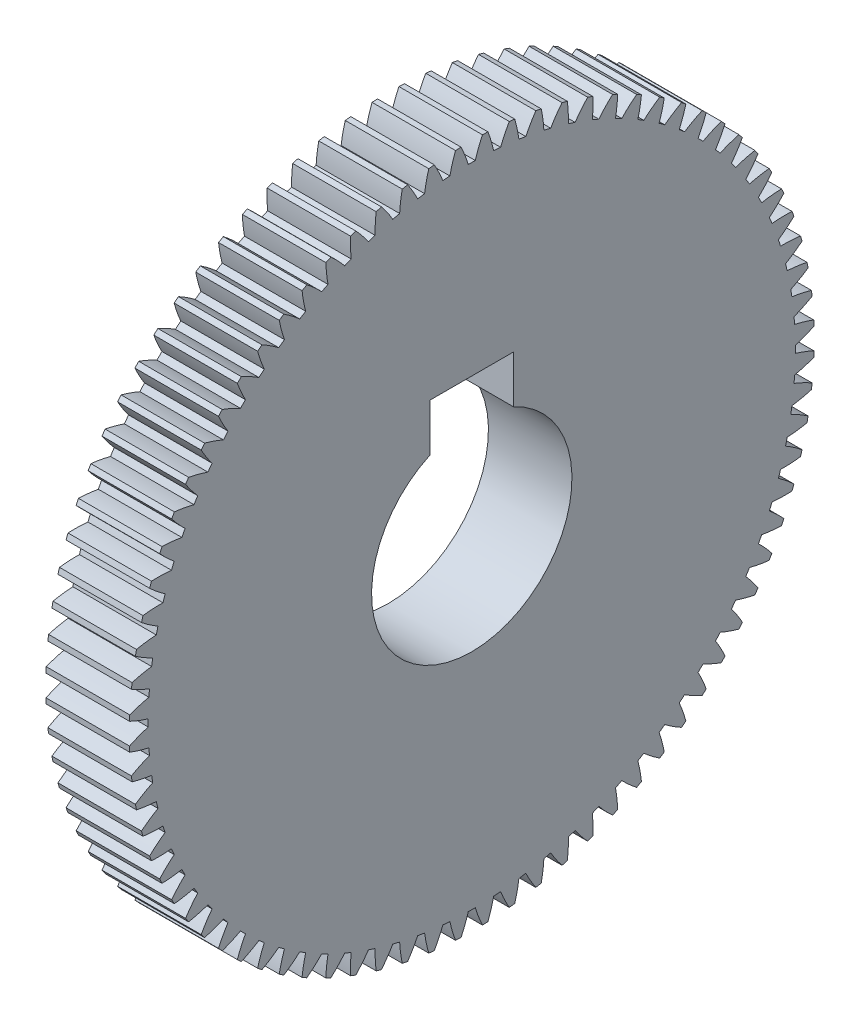
SolidWorks part; units mm, degrees
ref_plane "Plane1" through (0, 0, 0) normal (0, 0, 1) x (1, 0, 0)
ref_plane "Plane2" through (0, 0, 0) normal (0, 1, 0) x (1, 0, 0)
ref_plane "Plane3" through (0, 0, 0) normal (1, 0, 0) x (0, 0, -1)
other "Configuration Table"
sketch "HoldingSke" plane through (0, 0, 0) normal (0, 1, 0) x (1, 0, 0)
  line L0 (0, 0) -> (0.3473, -1.9696)
  line L1 (-15, 0) -> (100, 0) construction
  line L2 (0, 0) -> (-2.1039, 2.3779)
  line L3 (0, 0) -> (-11.863, 4.5341)
  line L4 (0, 0) -> (1.4996, 8.5048)
  line L5 (0, 0) -> (-46.8476, -17.4728)
  line L6 (0, 0) -> (-4.1448, -2.7965)
  line L7 (-2.1039, 2.3779) -> (8.6586, 51.2059)
  line L8 (-76.2, 54.61) -> (-73.9, 54.61)
  line L9 (-71.009, 38.7566) -> (-53.1078, 45.2721)
  line L10 (-76.2, 71.12) -> (104.1128, 71.12)
  line L11 (0, 0) -> (-5, 0)
  line L12 (-76.2, 101.6) -> (-76.181, 101.6)
  line L13 (24.9733, 27.94) -> (52.9518, 28.4284)
  line L14 (24.9733, 27.94) -> (24.9743, 27.94)
  line L15 (24.9733, 27.94) -> (100.4006, 29.5858)
  line L16 (-63.627, -0.5) -> (-12.827, -0.5)
  circle A0 centre (0, 0) radius 6
  circle A1 centre (0, 0) radius 19.374
  circle A2 centre (0, 0) radius 37.5
  circle A3 centre (0, 0) radius 6
  dimension "MHD" = 38.748
  dimension "Hub_dia" = 75
  dimension "Bore" = 12
  dimension "MBD" = 12
  dimension "Num_teeth" = 80
  dimension "Pitch" = 2
  dimension "Overall_len" = 50
  dimension "Show_teeth" = 80
  dimension "Thickness" = 5
  dimension "OAL" = 50.0001
  dimension "T_dim" = 2.3
  dimension "Ap" = 20
  dimension "H" = 19.05
  dimension "Pitch_radius" = 180.3128
  dimension "Width" = 5
  dimension "Backlash" = 0.019
  dimension "Addendum_fac" = 1
  dimension "Dedendum_fac" = 1.25
  dimension "Clearance_fac" = 0.25
  dimension "Dedendum_add" = 0.001
  dimension "Module" = 0.5
sketch "BasProSke" plane through (0, 0, 0) normal (0, 1, 0) x (1, 0, 0)
  line L0 (-10, 0) -> (60, 0) construction
  line L1 (0, 0) -> (0, 20.5)
  line L2 (0, 0) -> (5, 0)
  line L3 (5, 0) -> (5, 20.5)
  line L4 (5, 20.5) -> (0, 20.5)
  dimension "Thickness" = 5
  dimension "Diameter" = 41
revolve "Base-Revolve" add sketch "BasProSke" angle 360 about L0
sketch "TooCutSke" plane through (0, 0, 0) normal (1, 0, 0) x (0, 0, -1)
  line L1 (0, 0) -> (0, 107) construction
  line L2 (0, 0) -> (-0.4259, 19.9955) construction
  line L3 (0, 0) -> (-1.5701, 39.9627) construction
  line L4 (-0.4259, 19.9955) -> (-0.7851, 19.9814) construction
  arc A0 (0.2101, 19.3729) -> (-0.2101, 19.3729) centre (0, 0) ccw
  arc A1 (0.6519, 20.515) -> (-0.6519, 20.515) centre (0, 0) ccw
  circle A2 centre (0, 0) radius 20 construction
  circle A3 centre (0, 0) radius 18.7939 construction
  arc A4 (-0.2101, 19.3729) -> (-0.6519, 20.515) centre (-7.8705, 17.0665) ccw
  arc A5 (0.6519, 20.515) -> (0.2101, 19.3729) centre (7.8705, 17.0665) ccw
  dimension "Root_dia" = 38.748
  dimension "Overcut_dia" = 41.0508
  dimension "Pitch_dia" = 40
  dimension "Base_dia" = 37.5877
  dimension "Flank_rad" = 8
  dimension "Half_ang" = 2.25
  dimension "Half_CT" = 0.3594
extrude "ToothCut" cut sketch "TooCutSke" along normal through all
fillet "Breaks" [suppressed] radius 0.01
fillet "RootFillets" [suppressed] radius 0.126
pattern_circular "TeethCuts" count 80 every 4.5 about axis through (-10, 0, 0) along (1, 0, 0) of "ToothCut", "RootFillets", "Breaks"
sketch "HubNeaOneSke" plane through (0, 0, 0) normal (-1, 0, 0) x (0, 0, 1)
  circle A0 centre (0, 0) radius 19.374
  dimension "Diameter" = 38.748
extrude "HubNearOne" [suppressed] add sketch "HubNeaOneSke" along normal blind 45.0001
sketch "HubNeaBotSke" plane through (0, 0, 0) normal (-1, 0, 0) x (0, 0, 1)
  circle A0 centre (0, 0) radius 19.374
  dimension "Diameter" = 38.748
extrude "HubNearBoth" [suppressed] add sketch "HubNeaBotSke" along normal blind 22.5
ref_plane "FarPln" through (5, 0, 0) normal (1, 0, 0) x (0, 0, -1)
sketch "HubFarSke" plane through (5, 0, 0) normal (1, 0, 0) x (0, 0, -1)
  circle A0 centre (0, 0) radius 19.374
  dimension "Diameter" = 38.748
extrude "HubFar" [suppressed] add sketch "HubFarSke" along normal blind 22.5
sketch "BorSke" plane through (0, 0, 0) normal (1, 0, 0) x (0, 0, -1)
  circle A0 centre (0, 0) radius 6
  dimension "Diameter" = 12
extrude "Bore" cut sketch "BorSke" along normal mid plane 100.0001
sketch "KeySke" plane through (0, 0, 0) normal (1, 0, 0) x (0, 0, -1)
  line L0 (-2.5, 0) -> (-2.5, 8.3)
  line L1 (-2.5, 8.3) -> (2.5, 8.3)
  line L2 (2.5, 8.3) -> (2.5, 0)
  line L3 (0, 0) -> (0, 34) construction
  line L4 (-2.5, 0) -> (2.5, 0)
  dimension "Width" = 5
  dimension "Offset" = 8.3
extrude "Keyway" cut sketch "KeySke" along normal mid plane 100.0001
pattern_circular "Keyway2" [suppressed] count 2 every 90 about axis through (-10, 0, 0) along (1, 0, 0)
equation "' \"Module@HoldingSke\" = 6.35"
equation "' \"Num_teeth@HoldingSke\" = 12"
equation "' \"Ap@HoldingSke\" =  20"
equation "' \"Ap@HoldingSke\" = 20"
equation "' \"Width@HoldingSke\" = 0.5 * 25.4"
equation "' \"Hub_dia@HoldingSke\"= 1 * 25.4"
equation "' \"Hub_dia@HoldingSke\" = 1 * 25.4"
equation "' \"Overall_len@HoldingSke\" = 1.0 * 25.4"
equation "' \"Bore@HoldingSke\" = 0.75 * 25.4"
equation "' \"T_dim@HoldingSke\" = 0.1 * 25.4"
equation "' \"Width@KeySke\" = 0.25 * 25.4"
equation "' \"Show_teeth@HoldingSke\" = 13"
equation "' \"Backlash@HoldingSke\" = 0.009 * 25.4"
equation "' \"Addendum_fac@HoldingSke\" = 1.0"
equation "' \"Dedendum_fac@HoldingSke\" = 1.25"
equation "' \"Dedendum_add@HoldingSke\" = 0.00005 * 25.4"
equation "' \"Clearance_fac@HoldingSke\" = 0.25"
equation "\"Pitch@HoldingSke\" = 1 / \"Module@HoldingSke\""
equation "\"Overcut_dia@TooCutSke\" = (\"Num_teeth@HoldingSke\" + 2 * \"Addendum_fac@HoldingSke\") / \"Pitch@HoldingSke\" + 0.002 * 25.4"
equation "\"Pitch_dia@TooCutSke\" = \"Num_teeth@HoldingSke\" / \"Pitch@HoldingSke\""
equation "\"Base_dia@TooCutSke\" = \"Num_teeth@HoldingSke\" / \"Pitch@HoldingSke\" * cos((\"Ap@HoldingSke\"  * 3.14159265 / 180))"
equation "\"Root_dia@TooCutSke\" = (\"Num_teeth@HoldingSke\" + 2) / \"Pitch@HoldingSke\" - 2 * (\"Addendum_fac@HoldingSke\" + \"Dedendum_fac@HoldingSke\") / \"Pitch@HoldingSke\" - \"Dedendum_add@HoldingSke\" * 2"
equation "\"Half_ang@TooCutSke\" = 180 / \"Num_teeth@HoldingSke\""
equation "\"Half_CT@TooCutSke\" = \"Num_teeth@HoldingSke\" / \"Pitch@HoldingSke\" * sin((3.14159265 / 2 / \"Num_teeth@HoldingSke\")) / 2 - 7 * \"Backlash@HoldingSke\" / 4"
equation "\"Flank_rad@TooCutSke\" = \"Num_teeth@HoldingSke\" / \"Pitch@HoldingSke\" / 5"
equation "\"Radius@RootFillets\" = \"Clearance_fac@HoldingSke\" / \"Pitch@HoldingSke\" + \"Dedendum_add@HoldingSke\""
equation "\"Break_rad@Breaks\" = 0.02 / \"Pitch@HoldingSke\""
equation "\"Thickness@HoldingSke\" = \"Width@HoldingSke\""
equation "\"OAL@HoldingSke\" = \"Thickness@HoldingSke\""
equation "\"MHD@HoldingSke\" = (\"Num_teeth@HoldingSke\" + 2) / \"Pitch@HoldingSke\" - 2 * (\"Addendum_fac@HoldingSke\" + \"Dedendum_fac@HoldingSke\")  / \"Pitch@HoldingSke\" - \"Dedendum_add@HoldingSke\" * 2"
equation "\"MBD@HoldingSke\" = (\"Num_teeth@HoldingSke\" + 2) / \"Pitch@HoldingSke\" - 2 * (\"Addendum_fac@HoldingSke\" + \"Dedendum_fac@HoldingSke\")  / \"Pitch@HoldingSke\" - \"Dedendum_add@HoldingSke\" * 2 - 0.002 * 25.4"
equation "\"MHD@HoldingSke\" = ((sgn( \"MHD@HoldingSke\" - \"Hub_dia@HoldingSke\" )-1)*( \"MHD@HoldingSke\" - \"Hub_dia@HoldingSke\" ))/-2+ \"Hub_dia@HoldingSke\""
equation "\"MBD@HoldingSke\" = ((sgn( \"MBD@HoldingSke\" - \"Bore@HoldingSke\" )-1)*( \"MBD@HoldingSke\" - \"Bore@HoldingSke\" ))/-2+ \"Bore@HoldingSke\""
equation "\"OAL@HoldingSke\" = ((sgn( \"OAL@HoldingSke\" - \"Overall_len@HoldingSke\" )+1)*( \"OAL@HoldingSke\" - \"Overall_len@HoldingSke\" ))/2 + \"Overall_len@HoldingSke\" + 0.000002 * 25.4"
equation "\"Num_teeth@TeethCuts\" = int( \"Show_teeth@HoldingSke\" ) + 1"
equation "\"Num_teeth@TeethCuts\" = ((sgn( \"Num_teeth@TeethCuts\" - \"Num_teeth@HoldingSke\" )-1)*( \"Num_teeth@TeethCuts\" - \"Num_teeth@HoldingSke\" ))/-2+ \"Num_teeth@HoldingSke\""
equation "\"Num_teeth@TeethCuts\" = ((sgn( \"Num_teeth@TeethCuts\" - 2.0)+1)*( \"Num_teeth@TeethCuts\" - 2.0))/2 +2.0"
equation "\"Angle@TeethCuts\" = 360.0 / \"Num_teeth@HoldingSke\""
equation "\"Diameter@BasProSke\" = (\"Num_teeth@HoldingSke\" + 2 * \"Addendum_fac@HoldingSke\") / \"Pitch@HoldingSke\""
equation "\"Thickness@BasProSke\"  = \"Thickness@HoldingSke\""
equation "' \"Fillet_rad@BasProSke\" =  \"Thickness@HoldingSke\" * 0.05"
equation "' \"Fillet_rad@BasProSke\" = \"Thickness@HoldingSke\" * 0.05"
equation "\"MHD@HoldingSke\" = ((sgn( \"MHD@HoldingSke\" - \"Root_dia@TooCutSke\" )-1)*( \"MHD@HoldingSke\" - \"Root_dia@TooCutSke\" ))/-2+ \"Root_dia@TooCutSke\""
equation "\"Diameter@HubNeaOneSke\" = \"MHD@HoldingSke\""
equation "\"Length@HubNearOne\" = \"OAL@HoldingSke\" - \"Thickness@BasProSke\""
equation "\"Diameter@HubNeaBotSke\" = \"MHD@HoldingSke\""
equation "\"Length@HubNearBoth\" = ( \"OAL@HoldingSke\" - \"Thickness@BasProSke\" ) / 2.0"
equation "\"Thickness@FarPln\" = \"Thickness@BasProSke\""
equation "\"Diameter@HubFarSke\" = \"MHD@HoldingSke\""
equation "\"Length@HubFar\" = ( \"OAL@HoldingSke\" - \"Thickness@BasProSke\" ) / 2.0"
equation "\"Diameter@BorSke\" = \"MBD@HoldingSke\""
equation "\"D1@Bore\" = \"OAL@HoldingSke\" * 2.0"
equation "\"D1@Keyway\" = \"OAL@HoldingSke\" * 2.0"
equation "\"Offset@KeySke\" = \"T_dim@HoldingSke\" + \"MBD@HoldingSke\" / 2.0"
